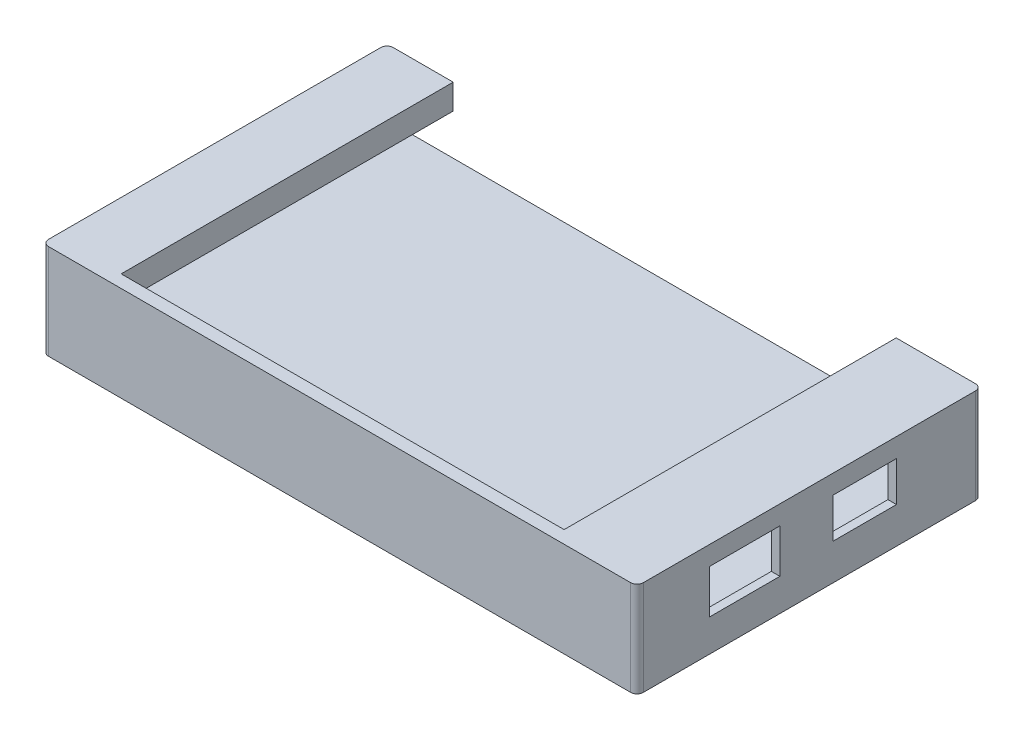
SolidWorks part; units mm, degrees
ref_plane "Front Plane" through (0, 0, 0) normal (0, 0, 1) x (1, 0, 0)
ref_plane "Top Plane" through (0, 0, 0) normal (0, 1, 0) x (1, 0, 0)
ref_plane "Right Plane" through (0, 0, 0) normal (1, 0, 0) x (0, 0, -1)
sketch "Sketch1" plane through (0, 0, 0) normal (0, 1, 0) x (1, 0, 0)
  line L1 (0, 0) -> (89.85, 0)
  line L2 (0, 0) -> (0, 50.4)
  line L3 (0, 50.4) -> (89.85, 50.4)
  line L4 (89.85, 0) -> (89.85, 50.4)
  line L5 (0, 0) -> (8.5, 0)
  line L6 (0, 0) -> (0, 50.4)
  line L7 (0, 50.4) -> (8.5, 50.4)
  line L8 (8.5, 0) -> (8.5, 50.4)
  line L9 (89.85, 0) -> (81.35, 0)
  line L10 (89.85, 0) -> (89.85, 50.4)
  line L11 (89.85, 50.4) -> (81.35, 50.4)
  line L12 (81.35, 0) -> (81.35, 50.4)
  line L13 (-2, 52.4) -> (91.85, 52.4)
  line L14 (-2, 52.4) -> (-2, -2)
  line L15 (-2, -2) -> (91.85, -2)
  line L16 (91.85, 52.4) -> (91.85, -2)
  point P13 (-2, 25.2)
  point P14 (0, 25.2)
  point P15 (44.925, -2)
  point P16 (44.925, 0)
  dimension "D1" = 50.4
  dimension "D2" = 89.85
  dimension "D3" = 8.5
  dimension "D4" = 8.5
  dimension "D5" = 2
  dimension "D6" = 2
  dimension "D7" = 2
extrude "Boss-Extrude1" add sketch "Sketch1" along normal blind 2 contours L16 L13 L14 L15 L4 L1 L2 L3 | L1 L8 L3 L2 | L1 L12 L3 L8 | L12 L1 L4 L3
sketch "Sketch2" plane through (0, 2, 0) normal (0, 1, 0) x (1, 0, 0)
  line L1 (0, 0) -> (86, 0)
  line L2 (0, 0) -> (0, 50)
  line L3 (0, 50) -> (86, 50)
  line L4 (86, 0) -> (86, 50)
  line L5 (-2, 52.4) -> (91.85, 52.4)
  line L6 (-2, 52.4) -> (-2, -2)
  line L7 (-2, -2) -> (91.85, -2)
  line L8 (91.85, 52.4) -> (91.85, -2)
  dimension "D1" = 50
  dimension "D2" = 86
extrude "Boss-Extrude2" add sketch "Sketch2" along normal blind 10 contours L2 L1 L4 L3 | L6 L5 L8 L7
sketch "Sketch3" plane through (0, 12, 0) normal (0, 1, 0) x (1, 0, 0)
  line L0 (-2, -2) -> (91.85, -2) construction
  line L1 (-2, 52.4) -> (8.45, 52.4)
  line L2 (-2, 52.4) -> (-2, -2)
  line L3 (-2, -2) -> (8.45, -2)
  line L4 (8.45, 52.4) -> (8.45, -2)
  line L5 (0, 0) -> (86, 0) construction
  line L6 (91.85, 52.4) -> (78.35, 52.4)
  line L7 (91.85, 52.4) -> (91.85, -2)
  line L8 (91.85, -2) -> (78.35, -2)
  line L9 (78.35, 52.4) -> (78.35, -2)
  line L10 (8.45, -2) -> (78.35, -2)
  line L11 (8.45, -2) -> (8.45, 0)
  line L12 (8.45, 0) -> (78.35, 0)
  line L13 (78.35, -2) -> (78.35, 0)
  line M6 (0, 0) -> (0, 50)
  line M7 (0, 50) -> (86, 50)
  line M8 (86, 50) -> (86, 0)
  line M9 (86, 0) -> (0, 0)
  line M10 (-2, -2) -> (91.85, -2)
  line M11 (91.85, -2) -> (91.85, 52.4)
  line M12 (91.85, 52.4) -> (-2, 52.4)
  line M13 (-2, 52.4) -> (-2, -2)
  dimension "D1" = 10.45
  dimension "D2" = 13.5
extrude "Boss-Extrude3" add sketch "Sketch3" along normal blind 3 contours L4 M7 M6 M9 | L4 M12 M13 M10 M9 M6 M7 | L9 L4 M9 M10 | L9 M7 M9 M8 | L9 M12 M7 M8 M9 M10 M11
sketch "Sketch5" plane through (86, 0, 0) normal (-1, 0, 0) x (0, 0, 1)
  line L0 (-50, 12) -> (-50, 2) construction
  line L1 (-50, 12) -> (0, 12)
  line L2 (-50, 12) -> (-50, 11.99)
  line L3 (-50, 11.99) -> (0, 11.99)
  line L4 (0, 12) -> (0, 11.99)
  line L5 (0, 12) -> (0, 2) construction
  line L7 (-50, 12) -> (-50, 2) construction
  line L8 (-9.45, 11.99) -> (-20.55, 11.99)
  line L9 (-9.45, 11.99) -> (-9.45, 5.09)
  line L10 (-9.45, 5.09) -> (-20.55, 5.09)
  line L11 (-20.55, 11.99) -> (-20.55, 5.09)
  line L12 (-38.95, 11.99) -> (-28.95, 11.99)
  line L13 (-38.95, 11.99) -> (-38.95, 5.7)
  line L14 (-38.95, 5.7) -> (-28.95, 5.7)
  line L15 (-28.95, 11.99) -> (-28.95, 5.7)
  dimension "D1" = 0.01
  dimension "D2" = 9.45
  dimension "D3" = 11.1
  dimension "D4" = 6.9
  dimension "D5" = 6.29
  dimension "D6" = 10
  dimension "D7" = 11.05
extrude "Cut-Extrude1" cut sketch "Sketch5" against normal up to surface (5.85 mm away) contours L15 L3 L13 L14 | L3 L11 L10 L9 up to face at (91.85, 7.5, -25.2)
sketch "Sketch6" plane through (0, 2, 0) normal (0, 1, 0) x (1, 0, 0)
  line L1 (0, 0) -> (86, 0)
  line L2 (0, 0) -> (0, 50)
  line L3 (0, 50) -> (86, 50)
  line L4 (86, 0) -> (86, 50)
extrude "Boss-Extrude4" add sketch "Sketch6" along normal blind 2.6
sketch "Sketch8" plane through (0, 0, -50) normal (0, 0, 1) x (1, 0, 0)
  line L0 (86, 12) -> (86, 4.6) construction
  line L1 (0, 4.6) -> (86, 4.6)
  line L2 (0, 4.6) -> (0, 12)
  line L3 (0, 12) -> (86, 12)
  line L4 (86, 4.6) -> (86, 12)
  line L5 (8.45, 12) -> (78.35, 12) construction
extrude "Cut-Extrude2" cut sketch "Sketch8" against normal up to surface (2.4 mm away) up to face at (44.1625, 10.5, -52.4)
sketch "Sketch9" plane through (0, 12, 0) normal (0, -1, 0) x (1, 0, 0)
  line L0 (86, 0) -> (86, -52.4) construction
  line L1 (78.35, -52.4) -> (86, -52.4)
  line L2 (78.35, -52.4) -> (78.35, 0)
  line L3 (78.35, 0) -> (86, 0)
  line L4 (86, -52.4) -> (86, 0)
  line L8 (0, 0) -> (0, -52.4) construction
  line L9 (8.45, -52.4) -> (0, -52.4)
  line L10 (8.45, -52.4) -> (8.45, 0)
  line L11 (8.45, 0) -> (0, 0)
  line L12 (0, -52.4) -> (0, 0)
  line L14 (8.45, -52.4) -> (0, -52.4) construction
  line L15 (0, 0) -> (8.45, 0) construction
  line L16 (8.45, -52.4) -> (8.45, 0) construction
  line L17 (78.35, -52.4) -> (78.35, 0) construction
extrude "Boss-Extrude5" add sketch "Sketch9" along normal blind 0.95
sketch "Sketch13" plane through (86, 0, 0) normal (-1, 0, 0) x (0, 0, 1)
  line L1 (-52.4, 4.6) -> (0, 4.6)
  line L2 (-52.4, 4.6) -> (-52.4, 11.05)
  line L3 (-52.4, 11.05) -> (0, 11.05)
  line L4 (0, 4.6) -> (0, 11.05)
  line L5 (0, 11.05) -> (0, 4.6) construction
  point P5 (0, 8.3101)
extrude "Cut-Extrude4" cut sketch "Sketch13" against normal blind 3 contours L2 L1 L4 L3
sketch "Sketch14" plane through (89, 0, 0) normal (-1, 0, 0) x (0, 0, 1)
  line L1 (-52.4, 4.6) -> (0, 4.6)
  line L2 (-52.4, 4.6) -> (-52.4, 11.05)
  line L3 (-52.4, 11.05) -> (0, 11.05)
  line L4 (0, 4.6) -> (0, 11.05)
  line L5 (0, 4.6) -> (0, 11.05) construction
  point P5 (0, 8.004)
  point P8 (0, 0)
extrude "Cut-Extrude5" cut sketch "Sketch14" against normal blind 1.5
fillet "Fillet1" radius 2 2 edges at (0, 7.825, 0) (90.5, 7.825, 0)
fillet "Fillet2" radius 1 4 edges at (-2, 7.5, -52.4) (91.85, 7.5, -52.4) (91.85, 7.5, 2) (-2, 7.5, 2)
ref_plane "Plane1" through (0, 0, -25.2) normal (0, 0, 1) x (1, 0, 0)
sketch "Sketch11" plane through (91.85, 0, 0) normal (1, 0, 0) x (0, 0, -1)
  line L0 (51.4, 0) -> (-1, 0) construction
  line L1 (12.633, 1) -> (19.633, 1)
  line L2 (12.633, 1) -> (12.633, 1.7)
  line L3 (12.633, 1.7) -> (19.633, 1.7)
  line L4 (19.633, 1) -> (19.633, 1.7)
  line L9 (14.633, 1) -> (17.633, 1)
  line L10 (14.633, 1) -> (14.633, 0)
  line L11 (14.633, 0) -> (17.633, 0)
  line L12 (17.633, 1) -> (17.633, 0)
  line L13 (-2, 0) -> (-2, 15) construction
  line L14 (25.2, 9.35) -> (25.2, -9.35) construction
  line L15 (35.767, 0) -> (32.767, 0)
  line L16 (32.767, 1) -> (32.767, 0)
  line L17 (35.767, 1) -> (32.767, 1)
  line L18 (35.767, 1) -> (35.767, 0)
  line L19 (37.767, 1.7) -> (30.767, 1.7)
  line L20 (30.767, 1) -> (30.767, 1.7)
  line L21 (37.767, 1) -> (30.767, 1)
  line L22 (37.767, 1) -> (37.767, 1.7)
  line L23 (38.95, 5.7) -> (28.95, 5.7) construction
  point P4 (3.0922, 0)
  point P5 (16.133, 1.7)
  point P18 (16.133, 0)
  point P19 (16.133, 1)
  point P20 (4.2313, 3.1687)
  line M21 (-1, 0) -> (51.4, 0)
  dimension "D1" = 4
  dimension "D2" = 18.133
  dimension "D3" = 3
  dimension "D4" = 7
  dimension "D5" = 1
extrude "Cut-Extrude3" [suppressed] cut sketch "Sketch11" against normal up to surface (93.85 mm away) contours L1 L4 L3 L2 | L12 L1 L10 M21 | L21 L22 L19 L20 L17 | L18 L17 L16 M21
